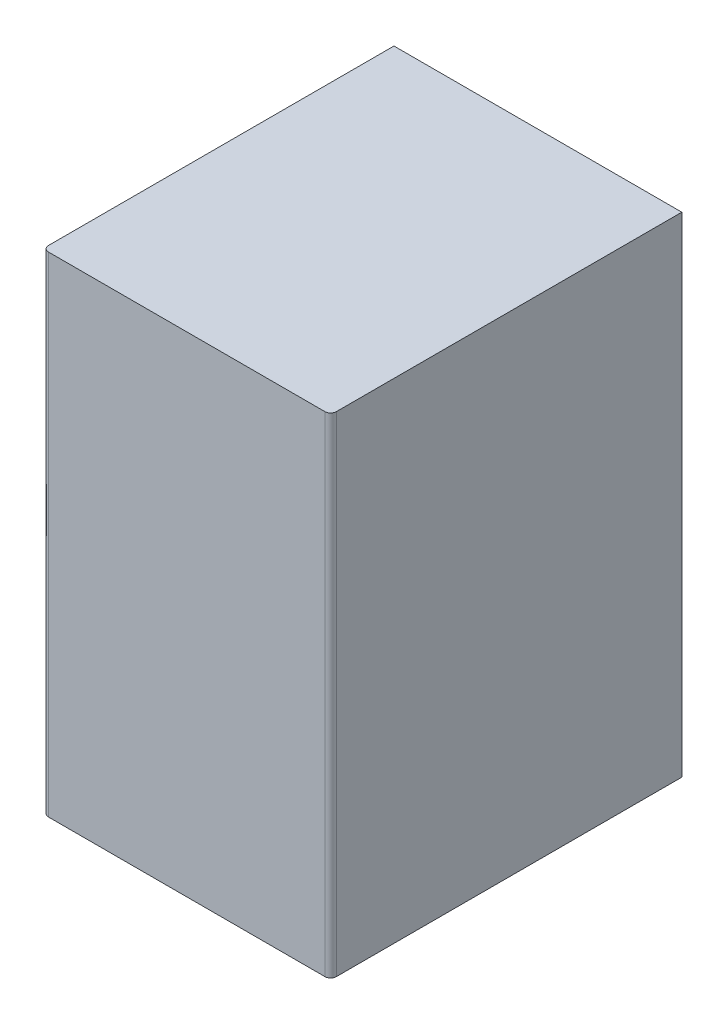
SolidWorks part; units mm, degrees
ref_plane "Front Plane" through (0, 0, 0) normal (0, 0, 1) x (1, 0, 0)
ref_plane "Top Plane" through (0, 0, 0) normal (0, 1, 0) x (1, 0, 0)
ref_plane "Right Plane" through (0, 0, 0) normal (1, 0, 0) x (0, 0, -1)
sketch "Sketch1" plane through (0, 0, 0) normal (0, 1, 0) x (1, 0, 0)
  line L1 (-250, 305) -> (250, 305)
  line L2 (-250, 305) -> (-250, -305)
  line L3 (-250, -305) -> (250, -305)
  line L4 (250, 305) -> (250, -305)
  line L5 (-250, 305) -> (250, -305) construction
  line L6 (-250, -305) -> (250, 305) construction
  point P0 (0, 0)
  dimension "D1" = 500
  dimension "D2" = 610
extrude "Boss-Extrude1" add sketch "Sketch1" along normal blind 850
fillet "Fillet1" radius 10 2 edges at (-250, 425, 305) (250, 425, 305)
